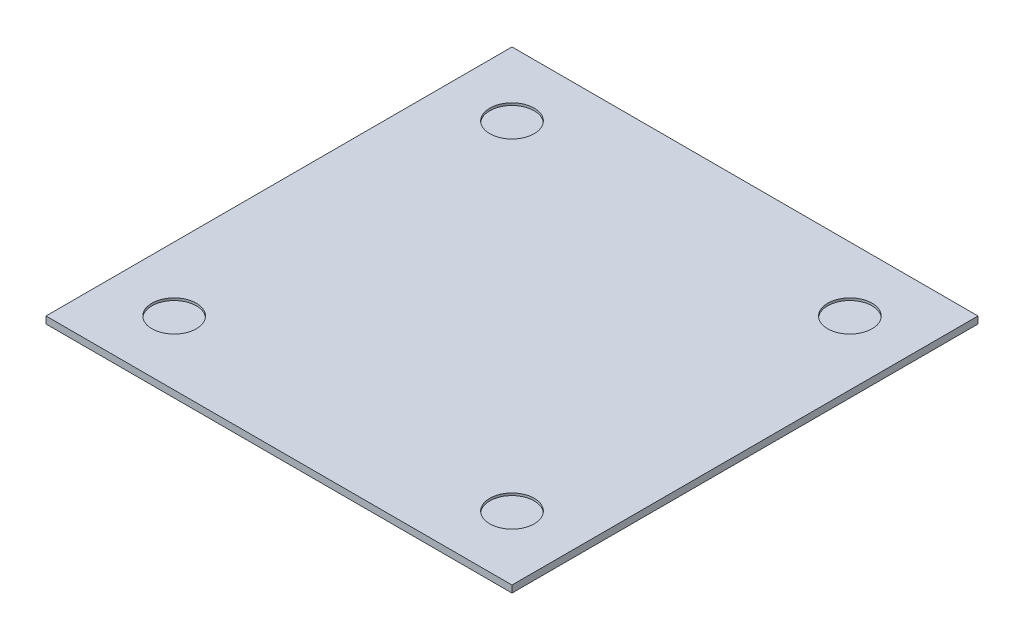
SolidWorks part; units mm, degrees
ref_plane "Front Plane" through (0, 0, 0) normal (0, 0, 1) x (1, 0, 0)
ref_plane "Top Plane" through (0, 0, 0) normal (0, 1, 0) x (1, 0, 0)
ref_plane "Right Plane" through (0, 0, 0) normal (1, 0, 0) x (0, 0, -1)
sketch "Sketch1" plane through (0, 0, 0) normal (0, 1, 0) x (1, 0, 0)
  line L1 (-100, 100) -> (100, 100)
  line L2 (-100, 100) -> (-100, -100)
  line L3 (-100, -100) -> (100, -100)
  line L4 (100, 100) -> (100, -100)
  line L5 (-100, 100) -> (100, -100) construction
  line L6 (-100, -100) -> (100, 100) construction
  point P0 (0, 0)
  dimension "D1" = 200
extrude "Boss-Extrude1" add sketch "Sketch1" along normal blind 3
sketch "Sketch2" plane through (0, 3, 0) normal (0, 1, 0) x (1, 0, 0)
  line L0 (-100, -100) -> (100, 100) construction
  line L1 (100, 100) -> (-100, 100) construction
  line L2 (-100, 100) -> (100, -100) construction
  line L3 (-72.5054, -72.5054) -> (-72.5054, 72.5054) construction
  line L4 (-72.5054, 72.5054) -> (72.5054, 72.5054) construction
  line L5 (72.5054, 72.5054) -> (72.5054, -72.5054) construction
  line L6 (72.5054, -72.5054) -> (-72.5054, -72.5054) construction
  circle A0 centre (-72.5054, 72.5054) radius 9.525
  circle A1 centre (72.5054, 72.5054) radius 9.525
  circle A2 centre (72.5054, -72.5054) radius 9.525
  circle A3 centre (-72.5054, -72.5054) radius 9.525
  dimension "D1" = 19.05
extrude "Cut-Extrude1" cut sketch "Sketch2" against normal blind 1
